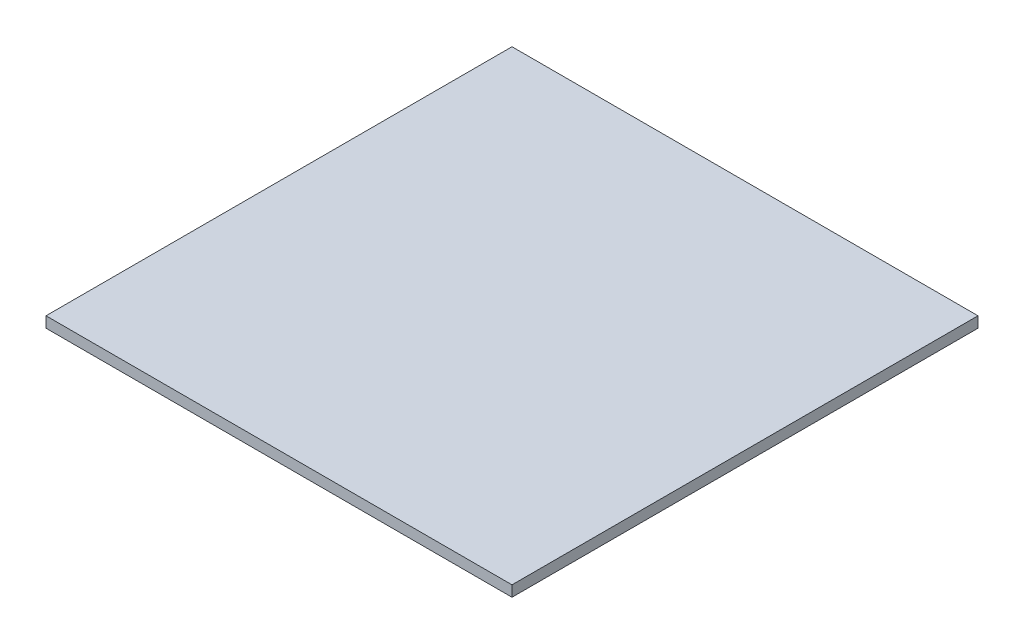
SolidWorks part; units mm, degrees
ref_plane "Front Plane" through (0, 0, 0) normal (0, 0, 1) x (1, 0, 0)
ref_plane "Top Plane" through (0, 0, 0) normal (0, 1, 0) x (1, 0, 0)
ref_plane "Right Plane" through (0, 0, 0) normal (1, 0, 0) x (0, 0, -1)
sketch "Sketch1" plane through (0, 0, 0) normal (0, 1, 0) x (1, 0, 0)
  line L1 (-99.0565, 160.8769) -> (142.2435, 160.8769)
  line L2 (-99.0565, 160.8769) -> (-99.0565, -80.4231)
  line L3 (-99.0565, -80.4231) -> (142.2435, -80.4231)
  line L4 (142.2435, 160.8769) -> (142.2435, -80.4231)
  dimension "D1" = 241.3
  dimension "D2" = 241.3
extrude "Boss-Extrude1" add sketch "Sketch1" along normal blind 5.588
